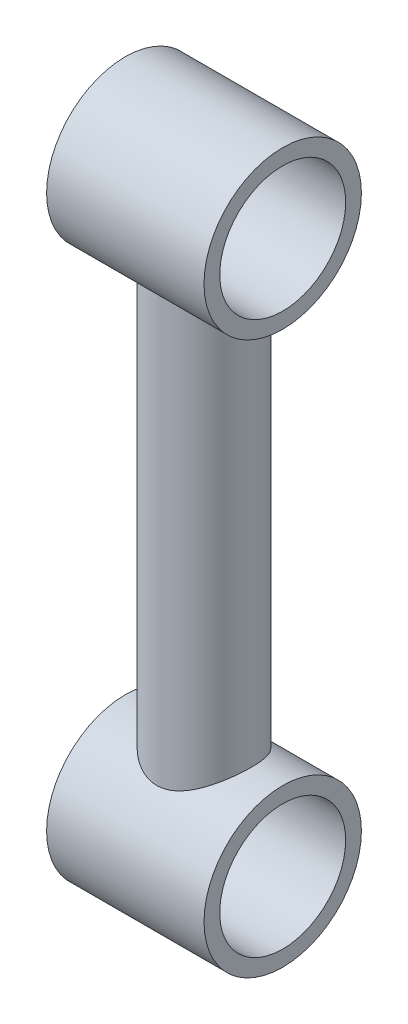
SolidWorks part; units mm, degrees
ref_plane "前视基准面" through (0, 0, 0) normal (0, 0, 1) x (1, 0, 0)
ref_plane "上视基准面" through (0, 0, 0) normal (0, 1, 0) x (1, 0, 0)
ref_plane "右视基准面" through (0, 0, 0) normal (1, 0, 0) x (0, 0, -1)
sketch "草图1" plane through (0, 0, 0) normal (1, 0, 0) x (0, 0, -1)
  circle A0 centre (0, 0) radius 40
  circle A1 centre (0, 0) radius 50
extrude "凸台-拉伸1" add sketch "草图1" along normal mid plane 100
ref_plane "基准面1" through (0, 175.5, 0) normal (0, 1, 0) x (1, 0, 0)
ref_point "点2"
sketch "草图2" plane through (0, 175.5, 0) normal (0, 1, 0) x (1, 0, 0)
  circle A0 centre (0, 0) radius 30
extrude "凸台-拉伸2" add sketch "草图2" against normal up to surface (135.5 mm away)
mirror "镜向2" about plane through (0, 175.5, 0) normal (0, 1, 0) of "凸台-拉伸1", "凸台-拉伸2"
